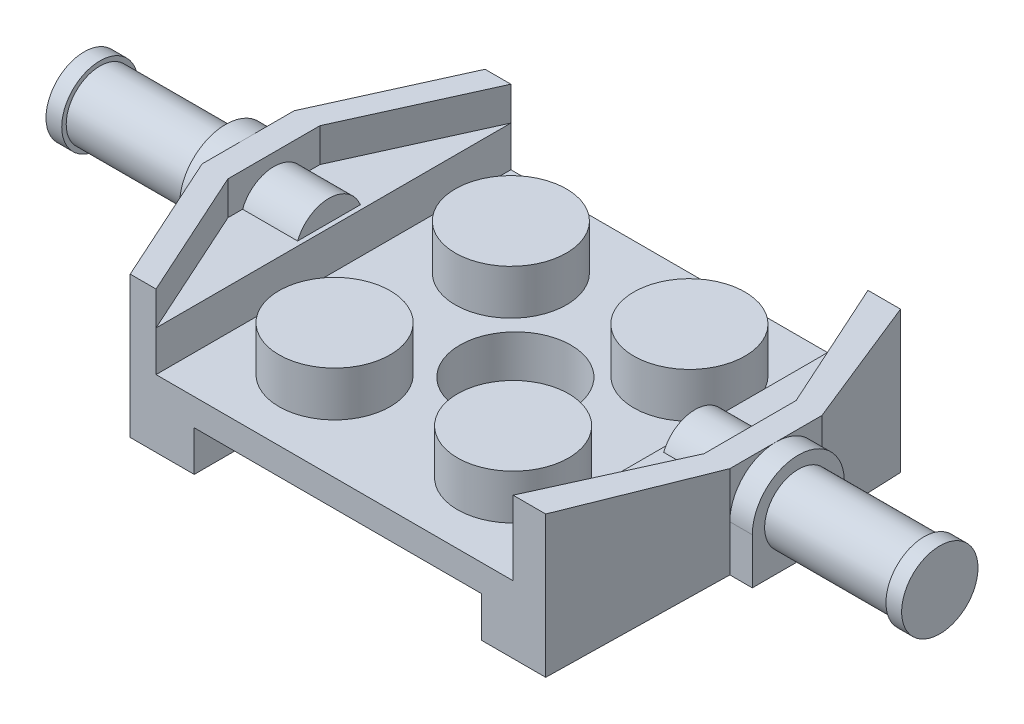
SolidWorks part; units mm, degrees
ref_plane "Front Plane" through (0, 0, 0) normal (0, 0, 1) x (1, 0, 0)
ref_plane "Top Plane" through (0, 0, 0) normal (0, 1, 0) x (1, 0, 0)
ref_plane "Right Plane" through (0, 0, 0) normal (1, 0, 0) x (0, 0, -1)
sketch "Sketch1" plane through (0, 0, 0) normal (0, 1, 0) x (1, 0, 0)
  line L1 (0, 0) -> (23.5, 0)
  line L2 (0, 0) -> (0, -15.8)
  line L3 (0, -15.8) -> (23.5, -15.8)
  line L4 (23.5, 0) -> (23.5, -15.8)
  dimension "D1" = 23.5
  dimension "D2" = 15.8
extrude "Boss-Extrude1" add sketch "Sketch1" along normal blind 6.3
sketch "Sketch3" plane through (0, 6.3, 0) normal (0, 1, 0) x (1, 0, 0)
  line L0 (0, 0) -> (23.5, -15.8) construction
  line L1 (23.5, 0) -> (0, -15.8) construction
  line L2 (0, -15.8) -> (23.5, -15.8) construction
  line L3 (3.8, 0) -> (19.7, 0)
  line L4 (3.8, 0) -> (3.8, -15.8)
  line L5 (3.8, -15.8) -> (19.7, -15.8)
  line L6 (19.7, 0) -> (19.7, -15.8)
  line L7 (3.8, 0) -> (19.7, -15.8) construction
  line L8 (3.8, -15.8) -> (19.7, 0) construction
  point P8 (11.75, -7.9)
  dimension "D1" = 15.9
extrude "Cut-Extrude1" cut sketch "Sketch3" against normal blind 3.3
sketch "Sketch4" plane through (0, 6.3, 0) normal (0, 1, 0) x (1, 0, 0)
  line L0 (21.15, 0) -> (23.5, -5.85)
  line L1 (23.5, 0) -> (19.7, 0) construction
  line L2 (23.5, -15.8) -> (23.5, 0) construction
  line L3 (23.5, -5.85) -> (23.5, 0)
  line L4 (23.5, 0) -> (21.15, 0)
  line L5 (21.15, -15.8) -> (23.5, -9.95)
  line L6 (19.7, -15.8) -> (23.5, -15.8) construction
  line L7 (23.5, -9.95) -> (23.5, -15.8)
  line L8 (23.5, -15.8) -> (21.15, -15.8)
  line L9 (2.65, -15.8) -> (0, -9.95)
  line L10 (0, -15.8) -> (3.8, -15.8) construction
  line L11 (0, 0) -> (0, -15.8) construction
  line L12 (0, -9.95) -> (0, -15.8)
  line L13 (0, -15.8) -> (2.65, -15.8)
  line L14 (0, 0) -> (0, -5.85)
  line L15 (0, -5.85) -> (2.65, 0)
  line L16 (3.8, 0) -> (0, 0) construction
  line L17 (2.65, 0) -> (0, 0)
  dimension "D1" = 18.5
  dimension "D2" = 18.5
  dimension "D3" = 5.85
  dimension "D4" = 5.85
  dimension "D5" = 5.85
  dimension "D6" = 5.85
  dimension "D7" = 1.15
  dimension "D8" = 1.45
  dimension "D9" = 1.15
extrude "Cut-Extrude2" cut sketch "Sketch4" against normal through all
sketch "Sketch5" plane through (0, 6.3, 0) normal (0, 1, 0) x (1, 0, 0)
  line L0 (3.8, 0) -> (1.15, -5.85)
  line L1 (1.15, -5.85) -> (1.15, -9.95)
  line L2 (1.15, -9.95) -> (3.8, -15.8)
  line L3 (3.8, -15.8) -> (3.8, 0)
  line L4 (19.7, 0) -> (19.7, -15.8)
  line L5 (19.7, -15.8) -> (22.35, -9.95)
  line L6 (22.35, -9.95) -> (22.35, -5.85)
  line L7 (22.35, -5.85) -> (19.7, 0)
  line L8 (23.5, -9.95) -> (23.5, -5.85) construction
  line L11 (0, -5.85) -> (0, -9.95) construction
  dimension "D1" = 1.45
  dimension "D2" = 1.15
  dimension "D3" = 1.15
  dimension "D4" = 0
  dimension "D5" = 0
  dimension "D6" = 0
extrude "Cut-Extrude3" cut sketch "Sketch5" against normal blind 1.5
sketch "Sketch7" plane through (0, 0, 15.8) normal (0, 0, 1) x (1, 0, 0)
  line L0 (0, 0) -> (0, 2.2)
  line L2 (0, 0) -> (0, 6.3) construction
  line L3 (0, 2.2) -> (2.65, 0)
  line L4 (11.9, 0) -> (11.9, 9.3877) construction
  line L5 (2.65, 0) -> (21.15, 0) construction
  line L6 (21.15, 0) -> (23.5, 0)
  line L7 (23.5, 0) -> (23.5, 2.2)
  line L8 (0, 0) -> (2.65, 0)
  line L9 (23.5, 0) -> (23.5, 6.3) construction
  line L10 (23.5, 2.2) -> (21.15, 0)
  line L11 (2.65, 0) -> (2.65, 6.3) construction
  dimension "D1" = 4.1
  dimension "D2" = 4.1
extrude "Cut-Extrude4" cut sketch "Sketch7" against normal through all
sketch "Sketch8" plane through (23.5, 0, 0) normal (1, 0, 0) x (0, 0, -1)
  line L1 (-9.95, 4.25) -> (-9.95, 2.2)
  line L2 (-9.95, 2.2) -> (-5.85, 2.2)
  line L5 (-5.85, 2.2) -> (-5.85, 4.25)
  line L6 (-9.95, 6.3) -> (-5.85, 2.2) construction
  line L7 (-9.95, 2.2) -> (-5.85, 6.3) construction
  arc A0 (-5.85, 4.25) -> (-9.95, 4.25) centre (-7.9, 4.25) ccw
  dimension "D1" = 2.05
extrude "Boss-Extrude2" add sketch "Sketch8" along normal blind 1
sketch "Sketch9" plane through (24.5, 0, 0) normal (1, 0, 0) x (0, 0, -1)
  line L1 (-7.9, 6.3) -> (-5.85, 4.25) construction
  line L2 (-5.85, 4.25) -> (-9.95, 4.25) construction
  circle A2 centre (-7.9, 4.25) radius 1.5
  dimension "D1" = 3
extrude "Boss-Extrude3" add sketch "Sketch9" along normal blind 5.6 and the other way blind 4.6
sketch "Sketch10" plane through (0, 0, 0) normal (-1, 0, 0) x (0, 0, 1)
  line L0 (5.85, 2.2) -> (9.95, 2.2)
  line L1 (9.95, 2.2) -> (9.95, 4.25)
  line L2 (5.85, 2.2) -> (5.85, 4.25)
  line L3 (5.85, 6.3) -> (9.95, 2.2) construction
  line L4 (5.85, 2.2) -> (9.95, 6.3) construction
  line L5 (9.95, 2.2) -> (9.95, 6.3) construction
  arc A0 (9.95, 4.25) -> (5.85, 4.25) centre (7.9, 4.25) ccw
  dimension "D1" = 2.05
extrude "Boss-Extrude4" add sketch "Sketch10" along normal blind 1
sketch "Sketch11" plane through (-1, 0, 0) normal (-1, 0, 0) x (0, 0, 1)
  line L0 (5.85, 4.25) -> (9.95, 4.25) construction
  line L1 (9.95, 6.3) -> (9.95, 4.25) construction
  line L2 (9.95, 4.25) -> (7.9, 6.3) construction
  line L3 (7.9, 6.3) -> (9.95, 6.3) construction
  circle A0 centre (7.9, 4.25) radius 2.05 construction
  circle A1 centre (7.9, 4.25) radius 1.5
  dimension "D1" = 3
extrude "Boss-Extrude5" add sketch "Sketch11" along normal blind 5.6 and the other way blind 4.6
sketch "Sketch12" plane through (0, 0, 0) normal (0, -1, 0) x (1, 0, 0)
  line L0 (2.65, 15.8) -> (21.15, 0) construction
  line L1 (21.15, 0) -> (21.15, 15.8) construction
  line L2 (21.15, 15.8) -> (2.65, 0) construction
  line L3 (21.15, 0) -> (2.65, 0) construction
  line L4 (5.5, 15.8) -> (18.3, 15.8)
  line L5 (5.5, 15.8) -> (5.5, 0)
  line L6 (5.5, 0) -> (18.3, 0)
  line L7 (18.3, 15.8) -> (18.3, 0)
  line L8 (5.5, 15.8) -> (18.3, 0) construction
  line L9 (5.5, 0) -> (18.3, 15.8) construction
  line L11 (5.5, 8.5) -> (8.7568, 8.5)
  line L12 (5.5, 8.5) -> (5.5, 7.3)
  line L13 (5.5, 7.3) -> (8.7568, 7.3)
  line L14 (18.3, 8.5) -> (18.3, 7.3)
  line L15 (5.5, 8.5) -> (18.3, 7.3) construction
  line L16 (5.5, 7.3) -> (18.3, 8.5) construction
  line L18 (15.0376, 8.5289) -> (18.3, 8.5)
  line L19 (15.0432, 7.3) -> (18.3, 7.3)
  arc A0 (8.7568, 7.3) -> (15.0432, 7.3) centre (11.9, 7.9) ccw
  arc A1 (15.0376, 8.5289) -> (8.7568, 8.5) centre (11.9, 7.9) ccw
  point P6 (11.9, 7.9)
  point P15 (11.9, 7.9)
  line M1 (21.15, 15.8) -> (2.65, 15.8)
  line M3 (2.65, 0) -> (21.15, 0)
  dimension "D3" = 6.4
  dimension "D1" = 12.8
  dimension "D2" = 1.2
extrude "Cut-Extrude5" cut sketch "Sketch12" against normal blind 1.8 contours A1 L18 L7 L5 L11 M1 | A0 L13 L5 L7 L19 M3
sketch "Sketch13" plane through (0, 0, 0) normal (0, -1, 0) x (1, 0, 0)
  line L1 (2.65, 7.9) -> (21.15, 7.9) construction
  line L2 (2.65, 0) -> (2.65, 15.8) construction
  line L3 (21.15, 0) -> (21.15, 15.8) construction
  line L4 (11.9, 0) -> (11.9, 15.8) construction
  line L5 (5.5, 0) -> (18.3, 0) construction
  line L6 (18.3, 15.8) -> (5.5, 15.8) construction
  circle A2 centre (11.9, 7.9) radius 2.475
  dimension "D1" = 4.95
extrude "Cut-Extrude6" cut sketch "Sketch13" against normal through all
sketch "Sketch14" plane through (0, 0, 0) normal (0, -1, 0) x (1, 0, 0)
  line L0 (4, 13.5673) -> (4, 2.2327)
  line L1 (1.5, 8.45) -> (3.7121, 13.6262)
  line L2 (1.5, 7.35) -> (1.5, 8.45)
  line L3 (3.7121, 2.1738) -> (1.5, 7.35)
  line L4 (5.5, 7.3) -> (5.5, 0) construction
  line L5 (0, 7.9) -> (0, 5.85) construction
  line L8 (11.9, 15.8) -> (11.9, -1.9142) construction
  line L9 (18.3, 15.8) -> (5.5, 15.8) construction
  line L10 (20.0879, 2.1738) -> (22.3, 7.35)
  line L11 (22.3, 7.35) -> (22.3, 8.45)
  line L12 (22.3, 8.45) -> (20.0879, 13.6262)
  line L13 (19.8, 13.5673) -> (19.8, 2.2327)
  line L14 (2.65, 15.8) -> (5.5, 15.8) construction
  line L15 (5.5, 0) -> (2.65, 0) construction
  arc A0 (19.8, 13.5673) -> (20.0879, 13.6262) centre (19.95, 13.5673) cw
  arc A1 (19.8, 2.2327) -> (20.0879, 2.1738) centre (19.95, 2.2327) ccw
  arc A2 (3.7121, 2.1738) -> (4, 2.2327) centre (3.85, 2.2327) ccw
  arc A3 (3.7121, 13.6262) -> (4, 13.5673) centre (3.85, 13.5673) cw
  point P26 (19.8, 14.3)
  point P29 (19.8, 1.5)
  point P32 (4, 1.5)
  point P35 (4, 14.3)
  dimension "D9" = 0.15
  dimension "D1" = 1.5
  dimension "D2" = 1.5
  dimension "D3" = 23.139
  dimension "D4" = 23.139
  dimension "D5" = 23.139
  dimension "D6" = 23.139
  dimension "D7" = 1.5
  dimension "D8" = 1.5
extrude "Cut-Extrude7" cut sketch "Sketch14" against normal blind 2.8
sketch "Sketch15" plane through (-6.6, 0, 0) normal (-1, 0, 0) x (0, 0, 1)
  line L0 (7.9, 5.75) -> (7.9, 2.75) construction
  circle A0 centre (7.9, 4.25) radius 1.5 construction
  circle A1 centre (7.9, 4.25) radius 1.5 construction
  circle A2 centre (7.9, 4.25) radius 1.7
  dimension "D1" = 3.4
extrude "Boss-Extrude7" add sketch "Sketch15" along normal blind 0.7
sketch "Sketch16" plane through (30.1, 0, 0) normal (1, 0, 0) x (0, 0, -1)
  line L0 (-7.9, 5.75) -> (-7.9, 2.75) construction
  circle A0 centre (-7.9, 4.25) radius 1.5 construction
  circle A1 centre (-7.9, 4.25) radius 1.5 construction
  circle A2 centre (-7.9, 4.25) radius 1.7
  dimension "D1" = 3.4
extrude "Boss-Extrude8" add sketch "Sketch16" along normal blind 0.7
sketch "Sketch17" plane through (0, 3, 0) normal (0, 1, 0) x (1, 0, 0)
  line L0 (3.8, -15.8) -> (19.7, -15.8) construction
  line L1 (19.7, 0) -> (3.8, 0) construction
  line L2 (19.7, 0) -> (19.7, -15.8) construction
  line L3 (3.8, -15.8) -> (3.8, 0) construction
  line L4 (3.8, 0) -> (3.8, -15.8) construction
  circle A0 centre (7.775, -3.975) radius 2.475
  circle A1 centre (7.775, -11.825) radius 2.475
  circle A2 centre (15.725, -11.825) radius 2.475
  circle A3 centre (15.725, -3.975) radius 2.475
  dimension "D1" = 4.95
  dimension "D2" = 4.95
  dimension "D3" = 4.95
  dimension "D4" = 4.95
  dimension "D5" = 3.975
  dimension "D11" = 3.975
  dimension "D6" = 3.975
  dimension "D7" = 3.975
  dimension "D8" = 3.975
  dimension "D9" = 3.975
  dimension "D10" = 3.975
  dimension "D12" = 3.975
extrude "Boss-Extrude9" add sketch "Sketch17" along normal blind 2
